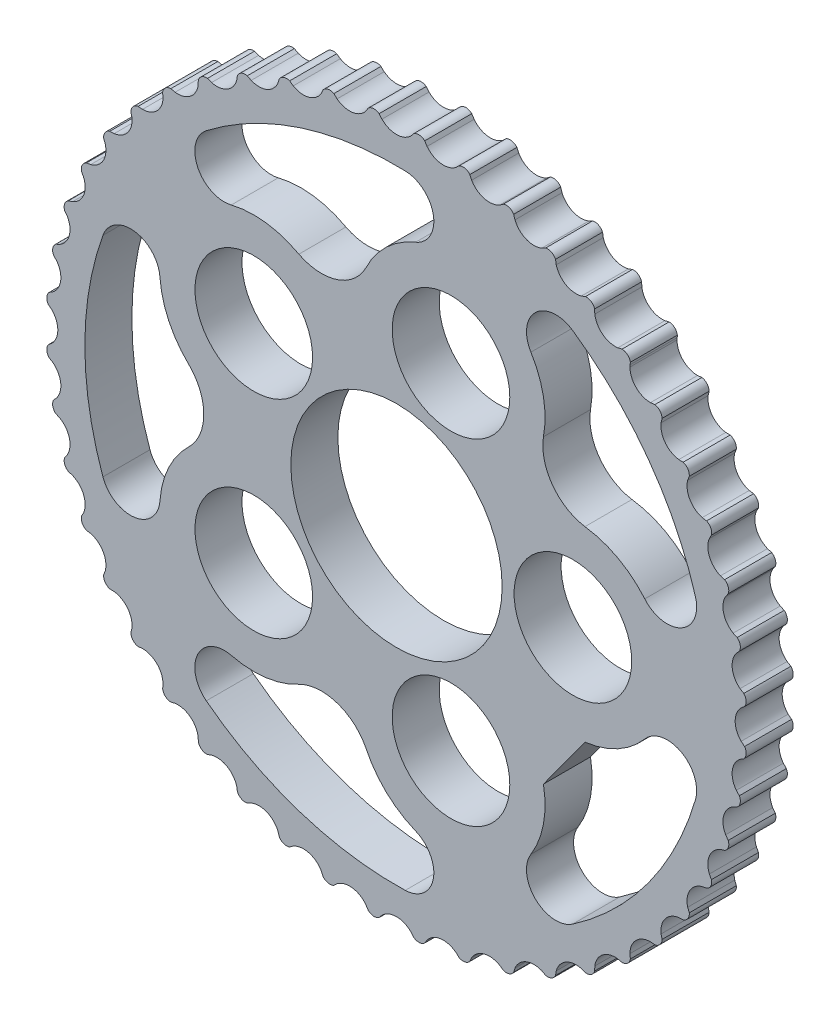
SolidWorks part; units mm, degrees
ref_plane "前视基准面" through (0, 0, 0) normal (0, 0, 1) x (1, 0, 0)
ref_plane "上视基准面" through (0, 0, 0) normal (0, 1, 0) x (1, 0, 0)
ref_plane "右视基准面" through (0, 0, 0) normal (1, 0, 0) x (0, 0, -1)
sketch "草图1" plane through (0, 0, 0) normal (0, 0, 1) x (1, 0, 0)
  line L0 (29.0079, 1.8987) -> (30.55, 0) construction
  line L1 (29.0079, -1.8987) -> (30.55, 0) construction
  line L2 (30.2894, -3.9821) -> (29.0079, -1.8987)
  line L3 (29.5973, -1.468) -> (29.3086, -1.2335)
  line L4 (29.5971, 1.4733) -> (29.3086, 1.2335)
  line L5 (29.5362, -2.4025) -> (29.2189, -2.6026)
  line L6 (29.1525, -5.3186) -> (28.8969, -5.0485)
  line L7 (28.6292, -6.3942) -> (28.9699, -6.2372)
  line L8 (28.2089, -9.0783) -> (27.9907, -8.7771)
  line L9 (27.5496, -10.0763) -> (27.9079, -9.9652)
  line L10 (26.7826, -12.6826) -> (26.6056, -12.3555)
  line L11 (25.9987, -13.5861) -> (26.3685, -13.5226)
  line L12 (24.8981, -16.07) -> (24.7653, -15.7225)
  line L13 (24.003, -16.8634) -> (24.3778, -16.8487)
  line L14 (22.5875, -19.1823) -> (22.5012, -18.8205)
  line L15 (21.5965, -19.8521) -> (21.9701, -19.8865)
  line L16 (19.8905, -21.9665) -> (19.8521, -21.5965)
  line L17 (18.8205, -22.5012) -> (19.1864, -22.5841)
  line L18 (16.8531, -24.3748) -> (16.8634, -24.003)
  line L19 (15.7225, -24.7653) -> (16.0744, -24.8952)
  line L20 (13.5274, -26.366) -> (13.5861, -25.9987)
  line L21 (12.3555, -26.6056) -> (12.6874, -26.7803)
  line L22 (9.9702, -27.9061) -> (10.0763, -27.5496)
  line L23 (8.7771, -27.9907) -> (9.0834, -28.2073)
  line L24 (6.2424, -28.9688) -> (6.3942, -28.6292)
  line L25 (5.0485, -28.8969) -> (5.3239, -29.1516)
  line L26 (2.4078, -29.5357) -> (2.6026, -29.2189)
  line L27 (1.2335, -29.3086) -> (1.4733, -29.5971)
  line L28 (-1.468, -29.5973) -> (-1.2335, -29.3086)
  line L29 (-2.4025, -29.5362) -> (-2.6026, -29.2189)
  line L30 (-5.3186, -29.1525) -> (-5.0485, -28.8969)
  line L31 (-6.2372, -28.9699) -> (-6.3942, -28.6292)
  line L32 (-9.0783, -28.2089) -> (-8.7771, -27.9907)
  line L33 (-10.0763, -27.5496) -> (-9.9652, -27.9079)
  line L34 (-12.6826, -26.7826) -> (-12.3555, -26.6056)
  line L35 (-13.5226, -26.3685) -> (-13.5861, -25.9987)
  line L36 (-16.07, -24.8981) -> (-15.7225, -24.7653)
  line L37 (-16.8634, -24.003) -> (-16.8487, -24.3778)
  line L38 (-19.1823, -22.5875) -> (-18.8205, -22.5012)
  line L39 (-19.8865, -21.9701) -> (-19.8521, -21.5965)
  line L40 (-21.9665, -19.8905) -> (-21.5965, -19.8521)
  line L41 (-22.5841, -19.1864) -> (-22.5012, -18.8205)
  line L42 (-24.3748, -16.8531) -> (-24.003, -16.8634)
  line L43 (-24.8952, -16.0744) -> (-24.7653, -15.7225)
  line L44 (-26.366, -13.5274) -> (-25.9987, -13.5861)
  line L45 (-26.7803, -12.6874) -> (-26.6056, -12.3555)
  line L46 (-27.9061, -9.9702) -> (-27.5496, -10.0763)
  line L47 (-28.2073, -9.0834) -> (-27.9907, -8.7771)
  line L48 (-28.9688, -6.2424) -> (-28.6292, -6.3942)
  line L49 (-28.8969, -5.0485) -> (-29.1516, -5.3239)
  line L50 (-29.5357, -2.4078) -> (-29.2189, -2.6026)
  line L51 (-29.3086, -1.2335) -> (-29.5971, -1.4733)
  line L52 (-29.5973, 1.468) -> (-29.3086, 1.2335)
  line L53 (-29.5362, 2.4025) -> (-29.2189, 2.6026)
  line L54 (-29.1525, 5.3186) -> (-28.8969, 5.0485)
  line L55 (-28.9699, 6.2372) -> (-28.6292, 6.3942)
  line L56 (-28.2089, 9.0783) -> (-27.9907, 8.7771)
  line L57 (-27.9079, 9.9652) -> (-27.5496, 10.0763)
  line L58 (-26.7826, 12.6826) -> (-26.6056, 12.3555)
  line L59 (-26.3685, 13.5226) -> (-25.9987, 13.5861)
  line L60 (-24.8981, 16.07) -> (-24.7653, 15.7225)
  line L61 (-24.3778, 16.8487) -> (-24.003, 16.8634)
  line L62 (-22.5875, 19.1823) -> (-22.5012, 18.8205)
  line L63 (-21.9701, 19.8865) -> (-21.5965, 19.8521)
  line L64 (-19.8905, 21.9665) -> (-19.8521, 21.5965)
  line L65 (-19.1864, 22.5841) -> (-18.8205, 22.5012)
  line L66 (-16.8531, 24.3748) -> (-16.8634, 24.003)
  line L67 (-15.7225, 24.7653) -> (-16.0744, 24.8952)
  line L68 (-13.5274, 26.366) -> (-13.5861, 25.9987)
  line L69 (-12.6874, 26.7803) -> (-12.3555, 26.6056)
  line L70 (-9.9702, 27.9061) -> (-10.0763, 27.5496)
  line L71 (-9.0834, 28.2073) -> (-8.7771, 27.9907)
  line L72 (-6.2424, 28.9688) -> (-6.3942, 28.6292)
  line L73 (-5.3239, 29.1516) -> (-5.0485, 28.8969)
  line L74 (-2.4078, 29.5357) -> (-2.6026, 29.2189)
  line L75 (-1.4733, 29.5971) -> (-1.2335, 29.3086)
  line L76 (1.468, 29.5973) -> (1.2335, 29.3086)
  line L77 (2.4025, 29.5362) -> (2.6026, 29.2189)
  line L78 (5.3186, 29.1525) -> (5.0485, 28.8969)
  line L79 (6.2372, 28.9699) -> (6.3942, 28.6292)
  line L80 (9.0783, 28.2089) -> (8.7771, 27.9907)
  line L81 (9.9652, 27.9079) -> (10.0763, 27.5496)
  line L82 (12.6826, 26.7826) -> (12.3555, 26.6056)
  line L83 (13.5226, 26.3685) -> (13.5861, 25.9987)
  line L84 (16.07, 24.8981) -> (15.7225, 24.7653)
  line L85 (16.8487, 24.3778) -> (16.8634, 24.003)
  line L86 (19.1823, 22.5875) -> (18.8205, 22.5012)
  line L87 (19.8521, 21.5965) -> (19.8713, 21.7815)
  line L88 (21.9665, 19.8905) -> (21.5965, 19.8521)
  line L89 (22.5841, 19.1864) -> (22.5012, 18.8205)
  line L90 (24.3748, 16.8531) -> (24.003, 16.8634)
  line L91 (24.7653, 15.7225) -> (24.8952, 16.0744)
  line L92 (26.366, 13.5274) -> (25.9987, 13.5861)
  line L93 (26.6056, 12.3555) -> (26.7803, 12.6874)
  line L94 (27.9061, 9.9702) -> (27.5496, 10.0763)
  line L95 (27.9907, 8.7771) -> (28.2073, 9.0834)
  line L96 (28.9688, 6.2424) -> (28.6292, 6.3942)
  line L97 (29.1516, 5.3239) -> (28.8969, 5.0485)
  line L98 (29.5357, 2.4078) -> (29.2189, 2.6026)
  line L99 (12.4976, -12.7883) -> (16.0243, -7.9342)
  line L108 (19.8865, 21.9701) -> (19.8713, 21.7815)
  circle A0 centre (0, 0) radius 8.985
  circle A1 centre (15, 0) radius 5
  circle A2 centre (4.6353, -14.2658) radius 5
  circle A3 centre (-12.1353, -8.8168) radius 5
  circle A4 centre (-12.1353, 8.8168) radius 5
  circle A5 centre (4.6353, 14.2658) radius 5
  circle A6 centre (0, 0) radius 30.55 construction
  circle A7 centre (30.55, 0) radius 1.75 construction
  circle A8 centre (0, 0) radius 29.07 construction
  circle A9 centre (29.0079, 1.8987) radius 0.73 construction
  circle A12 centre (29.0079, -1.8987) radius 0.73 construction
  arc A13 (29.3086, 1.2335) -> (29.3086, -1.2335) centre (30.55, 0) ccw
  circle A14 centre (30.2894, -3.9821) radius 1.75 construction
  arc A15 (29.5973, -1.468) -> (29.5362, -2.4025) centre (29.0079, -1.8987) cw
  arc A16 (29.2189, -2.6026) -> (28.8969, -5.0485) centre (30.2886, -3.9876) ccw
  arc A17 (29.1525, -5.3186) -> (28.9699, -6.2372) centre (28.5119, -5.6687) cw
  arc A18 (28.6292, -6.3942) -> (27.9907, -8.7771) centre (29.509, -7.9069) ccw
  arc A19 (28.2089, -9.0783) -> (27.9079, -9.9652) centre (27.5281, -9.3418) cw
  arc A20 (27.5496, -10.0763) -> (26.6056, -12.3555) centre (28.2245, -11.691) ccw
  arc A21 (26.7826, -12.6826) -> (26.3685, -13.5226) centre (26.0732, -12.855) cw
  arc A22 (25.9987, -13.5861) -> (24.7653, -15.7225) centre (26.4571, -15.275) ccw
  arc A23 (24.8981, -16.07) -> (24.3778, -16.8487) centre (24.1723, -16.1483) cw
  arc A24 (24.003, -16.8634) -> (22.5012, -18.8205) centre (24.2369, -18.5977) ccw
  arc A25 (22.5875, -19.1823) -> (21.9701, -19.8865) centre (21.8577, -19.1652) cw
  arc A26 (21.5965, -19.8521) -> (19.8521, -21.5965) centre (21.6021, -21.6021) ccw
  arc A27 (19.8905, -21.9665) -> (19.1864, -22.5841) centre (19.1691, -21.8543) cw
  arc A28 (18.8205, -22.5012) -> (16.8634, -24.003) centre (18.5977, -24.2369) ccw
  arc A29 (16.8531, -24.3748) -> (16.0744, -24.8952) centre (16.1526, -24.1694) cw
  arc A30 (15.7225, -24.7653) -> (13.5861, -25.9987) centre (15.275, -26.4571) ccw
  arc A31 (13.5274, -26.366) -> (12.6874, -26.7803) centre (12.8597, -26.0709) cw
  arc A32 (12.3555, -26.6056) -> (10.0763, -27.5496) centre (11.691, -28.2245) ccw
  arc A33 (9.9702, -27.9061) -> (9.0834, -28.2073) centre (9.3467, -27.5264) cw
  arc A34 (8.7771, -27.9907) -> (6.3942, -28.6292) centre (7.9069, -29.509) ccw
  arc A35 (6.2424, -28.9688) -> (5.3239, -29.1516) centre (5.6738, -28.5109) cw
  arc A36 (5.0485, -28.8969) -> (2.6026, -29.2189) centre (3.9876, -30.2886) ccw
  arc A37 (2.4078, -29.5357) -> (1.4733, -29.5971) centre (1.9039, -29.0076) cw
  arc A38 (1.2335, -29.3086) -> (-1.2335, -29.3086) centre (0, -30.55) ccw
  arc A39 (-1.468, -29.5973) -> (-2.4025, -29.5362) centre (-1.8987, -29.0079) cw
  arc A40 (-2.6026, -29.2189) -> (-5.0485, -28.8969) centre (-3.9876, -30.2886) ccw
  arc A41 (-5.3186, -29.1525) -> (-6.2372, -28.9699) centre (-5.6687, -28.5119) cw
  arc A42 (-6.3942, -28.6292) -> (-8.7771, -27.9907) centre (-7.9069, -29.509) ccw
  arc A43 (-9.0783, -28.2089) -> (-9.9652, -27.9079) centre (-9.3418, -27.5281) cw
  arc A44 (-10.0763, -27.5496) -> (-12.3555, -26.6056) centre (-11.691, -28.2245) ccw
  arc A45 (-12.6826, -26.7826) -> (-13.5226, -26.3685) centre (-12.855, -26.0732) cw
  arc A46 (-13.5861, -25.9987) -> (-15.7225, -24.7653) centre (-15.275, -26.4571) ccw
  arc A47 (-16.07, -24.8981) -> (-16.8487, -24.3778) centre (-16.1483, -24.1723) cw
  arc A48 (-16.8634, -24.003) -> (-18.8205, -22.5012) centre (-18.5977, -24.2369) ccw
  arc A49 (-19.1823, -22.5875) -> (-19.8865, -21.9701) centre (-19.1652, -21.8577) cw
  arc A50 (-19.8521, -21.5965) -> (-21.5965, -19.8521) centre (-21.6021, -21.6021) ccw
  arc A51 (-21.9665, -19.8905) -> (-22.5841, -19.1864) centre (-21.8543, -19.1691) cw
  arc A52 (-22.5012, -18.8205) -> (-24.003, -16.8634) centre (-24.2369, -18.5977) ccw
  arc A53 (-24.3748, -16.8531) -> (-24.8952, -16.0744) centre (-24.1694, -16.1526) cw
  arc A54 (-24.7653, -15.7225) -> (-25.9987, -13.5861) centre (-26.4571, -15.275) ccw
  arc A55 (-26.366, -13.5274) -> (-26.7803, -12.6874) centre (-26.0709, -12.8597) cw
  arc A56 (-26.6056, -12.3555) -> (-27.5496, -10.0763) centre (-28.2245, -11.691) ccw
  arc A57 (-27.9061, -9.9702) -> (-28.2073, -9.0834) centre (-27.5264, -9.3467) cw
  arc A58 (-27.9907, -8.7771) -> (-28.6292, -6.3942) centre (-29.509, -7.9069) ccw
  arc A59 (-28.9688, -6.2424) -> (-29.1516, -5.3239) centre (-28.5109, -5.6738) cw
  arc A60 (-28.8969, -5.0485) -> (-29.2189, -2.6026) centre (-30.2886, -3.9876) ccw
  arc A61 (-29.5357, -2.4078) -> (-29.5971, -1.4733) centre (-29.0076, -1.9039) cw
  arc A62 (-29.3086, -1.2335) -> (-29.3086, 1.2335) centre (-30.55, 0) ccw
  arc A63 (-29.5973, 1.468) -> (-29.5362, 2.4025) centre (-29.0079, 1.8987) cw
  arc A64 (-29.2189, 2.6026) -> (-28.8969, 5.0485) centre (-30.2886, 3.9876) ccw
  arc A65 (-29.1525, 5.3186) -> (-28.9699, 6.2372) centre (-28.5119, 5.6687) cw
  arc A66 (-28.6292, 6.3942) -> (-27.9907, 8.7771) centre (-29.509, 7.9069) ccw
  arc A67 (-28.2089, 9.0783) -> (-27.9079, 9.9652) centre (-27.5281, 9.3418) cw
  arc A68 (-27.5496, 10.0763) -> (-26.6056, 12.3555) centre (-28.2245, 11.691) ccw
  arc A69 (-26.7826, 12.6826) -> (-26.3685, 13.5226) centre (-26.0732, 12.855) cw
  arc A70 (-25.9987, 13.5861) -> (-24.7653, 15.7225) centre (-26.4571, 15.275) ccw
  arc A71 (-24.8981, 16.07) -> (-24.3778, 16.8487) centre (-24.1723, 16.1483) cw
  arc A72 (-24.003, 16.8634) -> (-22.5012, 18.8205) centre (-24.2369, 18.5977) ccw
  arc A73 (-22.5875, 19.1823) -> (-21.9701, 19.8865) centre (-21.8577, 19.1652) cw
  arc A74 (-21.5965, 19.8521) -> (-19.8521, 21.5965) centre (-21.6021, 21.6021) ccw
  arc A75 (-19.8905, 21.9665) -> (-19.1864, 22.5841) centre (-19.1691, 21.8543) cw
  arc A76 (-18.8205, 22.5012) -> (-16.8634, 24.003) centre (-18.5977, 24.2369) ccw
  arc A77 (-16.8531, 24.3748) -> (-16.0744, 24.8952) centre (-16.1526, 24.1694) cw
  arc A78 (-15.7225, 24.7653) -> (-13.5861, 25.9987) centre (-15.275, 26.4571) ccw
  arc A79 (-13.5274, 26.366) -> (-12.6874, 26.7803) centre (-12.8597, 26.0709) cw
  arc A80 (-12.3555, 26.6056) -> (-10.0763, 27.5496) centre (-11.691, 28.2245) ccw
  arc A81 (-9.9702, 27.9061) -> (-9.0834, 28.2073) centre (-9.3467, 27.5264) cw
  arc A82 (-8.7771, 27.9907) -> (-6.3942, 28.6292) centre (-7.9069, 29.509) ccw
  arc A83 (-6.2424, 28.9688) -> (-5.3239, 29.1516) centre (-5.6738, 28.5109) cw
  arc A84 (-5.0485, 28.8969) -> (-2.6026, 29.2189) centre (-3.9876, 30.2886) ccw
  arc A85 (-2.4078, 29.5357) -> (-1.4733, 29.5971) centre (-1.9039, 29.0076) cw
  arc A86 (-1.2335, 29.3086) -> (1.2335, 29.3086) centre (0, 30.55) ccw
  arc A87 (1.468, 29.5973) -> (2.4025, 29.5362) centre (1.8987, 29.0079) cw
  arc A88 (2.6026, 29.2189) -> (5.0485, 28.8969) centre (3.9876, 30.2886) ccw
  arc A89 (5.3186, 29.1525) -> (6.2372, 28.9699) centre (5.6687, 28.5119) cw
  arc A90 (6.3942, 28.6292) -> (8.7771, 27.9907) centre (7.9069, 29.509) ccw
  arc A91 (9.0783, 28.2089) -> (9.9652, 27.9079) centre (9.3418, 27.5281) cw
  arc A92 (10.0763, 27.5496) -> (12.3555, 26.6056) centre (11.691, 28.2245) ccw
  arc A93 (12.6826, 26.7826) -> (13.5226, 26.3685) centre (12.855, 26.0732) cw
  arc A94 (13.5861, 25.9987) -> (15.7225, 24.7653) centre (15.275, 26.4571) ccw
  arc A95 (16.07, 24.8981) -> (16.8487, 24.3778) centre (16.1483, 24.1723) cw
  arc A96 (16.8634, 24.003) -> (18.8205, 22.5012) centre (18.5977, 24.2369) ccw
  arc A97 (19.1823, 22.5875) -> (19.8865, 21.9701) centre (19.1652, 21.8577) cw
  arc A98 (19.8521, 21.5965) -> (21.5965, 19.8521) centre (21.6021, 21.6021) ccw
  arc A99 (21.9665, 19.8905) -> (22.5841, 19.1864) centre (21.8543, 19.1691) cw
  arc A100 (22.5012, 18.8205) -> (24.003, 16.8634) centre (24.2369, 18.5977) ccw
  arc A101 (24.3748, 16.8531) -> (24.8952, 16.0744) centre (24.1694, 16.1526) cw
  arc A102 (24.7653, 15.7225) -> (25.9987, 13.5861) centre (26.4571, 15.275) ccw
  arc A103 (26.366, 13.5274) -> (26.7803, 12.6874) centre (26.0709, 12.8597) cw
  arc A104 (26.6056, 12.3555) -> (27.5496, 10.0763) centre (28.2245, 11.691) ccw
  arc A105 (27.9061, 9.9702) -> (28.2073, 9.0834) centre (27.5264, 9.3467) cw
  arc A106 (27.9907, 8.7771) -> (28.6292, 6.3942) centre (29.509, 7.9069) ccw
  arc A107 (28.9688, 6.2424) -> (29.1516, 5.3239) centre (28.5109, 5.6738) cw
  arc A108 (28.8969, 5.0485) -> (29.2189, 2.6026) centre (30.2886, 3.9876) ccw
  arc A109 (29.5357, 2.4078) -> (29.5971, 1.4733) centre (29.0076, 1.9039) cw
  arc A116 (-8.3004, 15.8377) -> (-2.594, 17.6918) centre (-6.3743, 19.6179) ccw
  arc A123 (-8.3004, 15.8377) -> (-14.0494, 16.5844) centre (-12.1353, 8.8168) ccw
  arc A124 (16.0243, 7.9342) -> (21.1143, 5.159) centre (15, 0) cw
  arc A125 (-14.0494, 16.5844) -> (-16.1734, 20.9922) centre (-14.6476, 19.0118) cw
  arc A126 (-2.594, 17.6918) -> (1.6182, 21.6751) centre (4.6353, 14.2658) cw
  arc A127 (1.6182, 21.6751) -> (0.7457, 26.4895) centre (0.6753, 23.9905) ccw
  arc A128 (-16.1734, 20.9922) -> (0.7457, 26.4895) centre (0, 0) cw
  arc A129 (21.1143, 5.159) -> (25.4234, 7.4766) centre (23.025, 6.7712) ccw
  arc A130 (14.9669, 21.8687) -> (25.4234, 7.4766) centre (0, 0) cw
  arc A131 (11.4312, 18.4867) -> (14.9669, 21.8687) centre (13.5549, 19.8057) cw
  arc A132 (12.4976, 12.7883) -> (11.4312, 18.4867) centre (4.6353, 14.2658) ccw
  arc A133 (12.4976, 12.7883) -> (16.0243, 7.9342) centre (16.688, 12.1246) ccw
  arc A134 (12.4976, -12.7883) -> (11.4312, -18.4867) centre (4.6353, -14.2658) cw
  arc A135 (11.4312, -18.4867) -> (14.9669, -21.8687) centre (13.5549, -19.8057) ccw
  arc A136 (25.4234, -7.4766) -> (14.9669, -21.8687) centre (0, 0) cw
  arc A137 (21.1143, -5.159) -> (25.4234, -7.4766) centre (23.025, -6.7712) cw
  arc A138 (16.0243, -7.9342) -> (21.1143, -5.159) centre (15, 0) ccw
  arc A139 (16.0243, -7.9342) -> (12.4976, -12.7883) centre (16.688, -12.1246) ccw construction
  arc A140 (-8.3004, -15.8377) -> (-14.0494, -16.5844) centre (-12.1353, -8.8168) cw
  arc A141 (-14.0494, -16.5844) -> (-16.1734, -20.9922) centre (-14.6476, -19.0118) ccw
  arc A142 (0.7457, -26.4895) -> (-16.1734, -20.9922) centre (0, 0) cw
  arc A143 (1.6182, -21.6751) -> (0.7457, -26.4895) centre (0.6753, -23.9905) cw
  arc A144 (-2.594, -17.6918) -> (1.6182, -21.6751) centre (4.6353, -14.2658) ccw
  arc A145 (-2.594, -17.6918) -> (-8.3004, -15.8377) centre (-6.3743, -19.6179) ccw
  arc A146 (-17.6275, 3) -> (-20.1142, 8.2369) centre (-12.1353, 8.8168) cw
  arc A147 (-20.1142, 8.2369) -> (-24.9626, 8.8949) centre (-22.6076, 8.0557) ccw
  arc A148 (-24.9626, -8.8949) -> (-24.9626, 8.8949) centre (0, 0) cw
  arc A149 (-20.1142, -8.2369) -> (-24.9626, -8.8949) centre (-22.6076, -8.0557) cw
  arc A150 (-17.6275, -3) -> (-20.1142, -8.2369) centre (-12.1353, -8.8168) ccw
  arc A151 (-17.6275, -3) -> (-17.6275, 3) centre (-20.6275, 0) ccw
  dimension "D1" = 5
  dimension "D3" = 1.46
  dimension "D4" = 58.14
  dimension "D5" = 3.5
  dimension "D6" = 2.446
  dimension "D7" = 1.46
  dimension "D8" = 48
  dimension "D9" = 17.97
  dimension "D2" = 5
extrude "凸台-拉伸1" add sketch "草图1" along normal blind 4 contours A109 L98 A108 L97 A107 L96 A106 L95 A105 L94 A104 L93 A103 L92 A102 L91 A101 L90 A100 L89 A99 L88 A98 L87 L108 A97 L86 A96 L85 A95 L84 A94 L83 A93 L82 A92 L81 A91 L80 A90 L79 A89 L78 A88 L77 A87 L76 A86 L75 A85 L74
